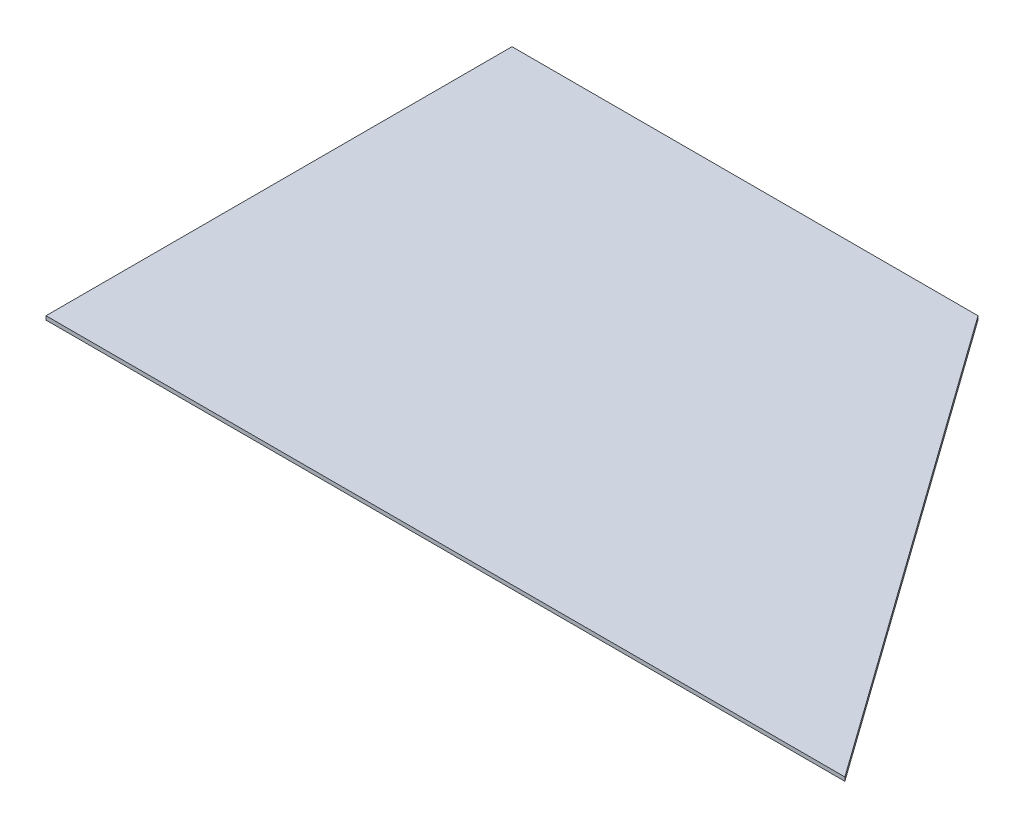
SolidWorks part; units mm, degrees
ref_plane "Front Plane" through (0, 0, 0) normal (0, 0, 1) x (1, 0, 0)
ref_plane "Top Plane" through (0, 0, 0) normal (0, 1, 0) x (1, 0, 0)
ref_plane "Right Plane" through (0, 0, 0) normal (1, 0, 0) x (0, 0, -1)
sketch "Sketch1" plane through (0, 0, 0) normal (0, 1, 0) x (1, 0, 0)
  line L0 (-17.5, 122.5) -> (17.5, 122.5)
  line L1 (17.5, 122.5) -> (105, 0)
  line L2 (105, 0) -> (-105, 0)
  line L3 (-105, 0) -> (-17.5, 122.5) construction
  line L4 (-105, 0) -> (-105, 122.5)
  line L5 (-105, 122.5) -> (-17.5, 122.5)
  point P2 (0, 0)
  dimension "D1" = 122.5
  dimension "D2" = 210
  dimension "D3" = 35
extrude "Boss-Extrude1" add sketch "Sketch1" along normal blind 1
